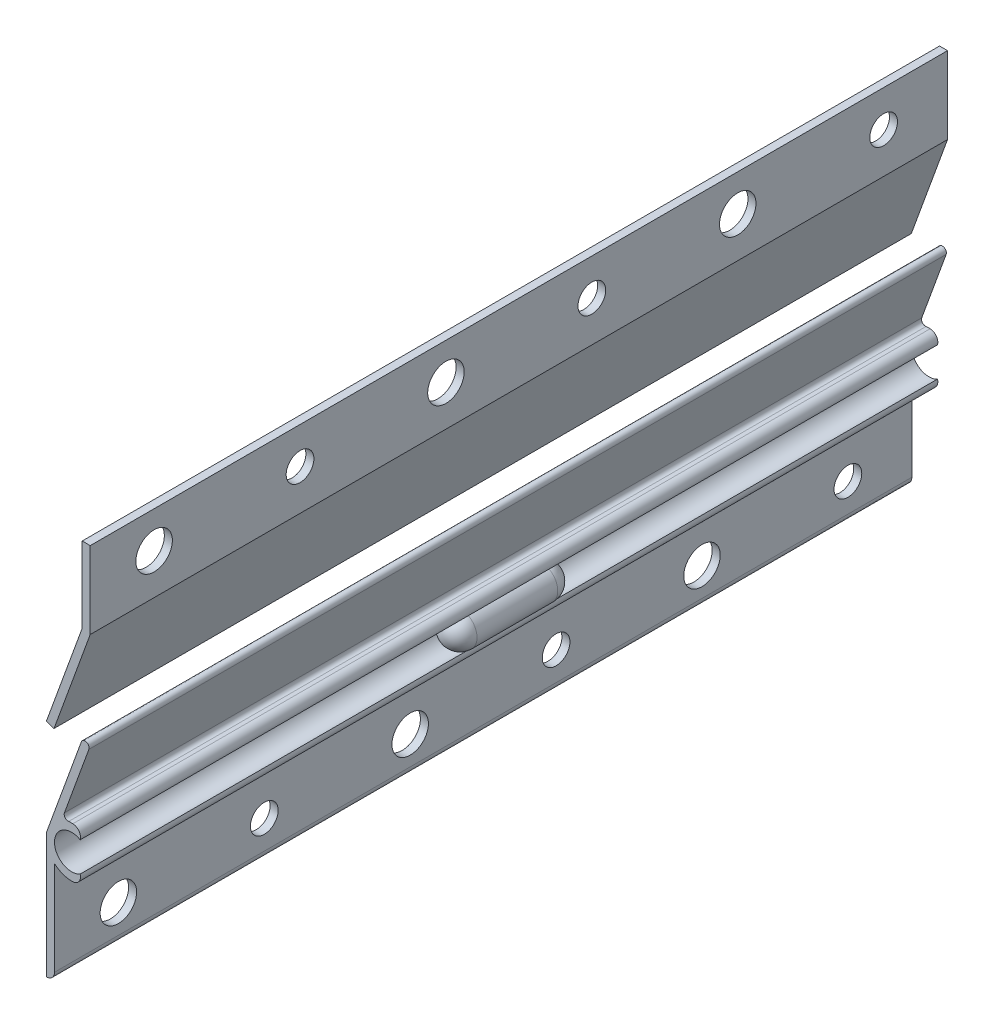
SolidWorks part; units mm, degrees
ref_plane "Front Plane" through (0, 0, 0) normal (0, 0, 1) x (1, 0, 0)
ref_plane "Top Plane" through (0, 0, 0) normal (0, 1, 0) x (1, 0, 0)
ref_plane "Right Plane" through (0, 0, 0) normal (1, 0, 0) x (0, 0, -1)
sketch "Sketch1" plane through (0, 0, 0) normal (0, 0, 1) x (1, 0, 0)
  line L0 (-3.81, -28.067) -> (-3.81, -6.2738) construction
  line L2 (-3.81, -28.067) -> (-2.413, -28.067) construction
  line L3 (-2.413, -28.067) -> (-2.413, -6.5201) construction
  line L4 (-2.413, -6.5201) -> (3.81, 10.5775) construction
  line L5 (3.81, 10.5775) -> (2.4972, 11.0553) construction
  line L6 (2.413, 28.067) -> (3.81, 28.067) construction
  line L7 (3.81, 28.067) -> (3.81, 14.662) construction
  line L9 (-2.4972, -2.667) -> (-3.81, -2.1892) construction
  line L10 (-3.81, -2.1892) -> (2.413, 14.9084) construction
  line L11 (2.413, 14.9084) -> (2.413, 28.067) construction
  line L12 (-3.81, -6.2738) -> (3.81, 14.662) construction
  line L13 (0, 28.067) -> (0, -28.067) construction
  line L14 (-3.81, 0) -> (3.81, 0) construction
  circle A0 centre (0.5689, -7.0459) radius 2.9819 construction
  circle A1 centre (0.5689, -7.0459) radius 4.3789 construction
  point P21 (0.5689, -2.667)
  dimension "Leaf Thickness" = 1.397
  dimension "Projection" = 7.62
  dimension "Length (C)" = 30.734
  dimension "Upper Leaf to Bottom" = 25.4
  dimension "D5" = 20
sketch "Sketch2" plane through (0, 0, 0) normal (1, 0, 0) x (0, 0, -1)
  line L0 (-74.6252, 28.067) -> (74.6252, 28.067) construction
  line L1 (-74.6252, 28.067) -> (-74.6252, 14.662) construction
  line L2 (-74.6252, 14.662) -> (74.6252, 14.662) construction
  line L3 (74.6252, 28.067) -> (74.6252, 14.662) construction
  line L4 (74.6252, -28.067) -> (-74.6252, -28.067) construction
  line L5 (74.6252, -28.067) -> (74.6252, -6.5201) construction
  line L6 (74.6252, -6.5201) -> (-74.6252, -6.5201) construction
  line L7 (-74.6252, -28.067) -> (-74.6252, -6.5201) construction
  line L8 (-12.7, 21.717) -> (12.7, 21.717) construction
  line L9 (0, 28.067) -> (0, -28.067) construction
  line L10 (-63.5, 21.717) -> (-63.5, 28.067) construction
  line L11 (-63.5, 21.717) -> (-38.1, 21.717) construction
  circle A0 centre (-63.5, 21.717) radius 3.175 construction
  circle A1 centre (-38.1, 21.717) radius 2.413 construction
  point P9 (152.4, 28.067)
  point P22 (0, -21.717)
  point P23 (0, 21.717)
  point P24 (-25.4, 21.717)
  point P25 (-50.8, 21.717)
  point P27 (25.4, 21.717)
  dimension "Large Mounting Hole" = 6.35
  dimension "Small Mounting Hole" = 4.826
  dimension "Length (A)" = 149.2504
  dimension "Hole Spacing" = 25.4
  dimension "Edge to Holes" = 6.35
  dimension "Number of Mounting Holes" = 304.8
  dimension "D5" = 6.35
  dimension "D1" = 50.8
  dimension "D2" = 25.4
  dimension "D3" = 38.1
sketch "Sketch3" plane through (0, 0, 0) normal (0, 0, 1) x (1, 0, 0)
  line L0 (-3.81, -2.1892) -> (-2.4972, -2.667)
  line L1 (-2.4972, -2.667) -> (3.81, 14.662)
  line L2 (3.81, 14.662) -> (3.81, 28.067)
  line L3 (3.81, 28.067) -> (2.413, 28.067)
  line L4 (2.413, 28.067) -> (2.413, 14.9084)
  line L5 (2.413, 14.9084) -> (-3.81, -2.1892)
extrude "Boss-Extrude1" add sketch "Sketch3" along normal up to vertex (74.6252 mm away) and the other way up to vertex (74.6252 mm away) up to point (0, 28.067, 74.6252) other way up to point (0, 28.067, -74.6252)
sketch "Sketch4" plane through (0, 0, 0) normal (0, 0, 1) x (1, 0, 0)
  line L0 (3.5711, 9.9211) -> (-0.6821, -1.7645)
  line L1 (-2.413, -10.2526) -> (-2.413, -26.67)
  line L3 (-3.81, -28.067) -> (-3.81, -6.2738)
  line L4 (-3.81, -6.2738) -> (2.2583, 10.3989)
  line L6 (-2.413, -6.5201) -> (3.81, 10.5775) construction
  line L7 (-3.81, -6.2738) -> (3.81, 14.662) construction
  line L8 (3.81, 10.5775) -> (2.4972, 11.0553) construction
  line L9 (-2.413, -28.067) -> (-2.413, -6.5201) construction
  line L10 (2.0598, -4.4635) -> (0.5689, -7.0459) construction
  arc A0 (2.2583, 10.3989) -> (3.5711, 9.9211) centre (2.9147, 10.16) cw
  arc A1 (-3.81, -28.067) -> (-2.413, -26.67) centre (-3.81, -26.67) ccw
  arc A3 (2.0598, -4.4635) -> (2.0598, -9.6282) centre (0.5689, -7.0459) ccw
  circle A4 centre (0.5689, -7.0459) radius 2.9819 construction
  arc A5 (-2.413, -10.2526) -> (0.7908, -11.4191) centre (0.5689, -7.0459) ccw
  arc A7 (2.0598, -9.6282) -> (0.7908, -11.4191) centre (0.72, -10.0239) cw
  arc A9 (-0.6821, -1.7645) -> (0.0561, -2.6971) centre (-0.0257, -2.0034) ccw
  arc A10 (0.0561, -2.6971) -> (0.7908, -2.6726) centre (0.5689, -7.0459) cw
  circle A11 centre (0.5689, -7.0459) radius 4.3789 construction
  arc A12 (2.0598, -4.4635) -> (0.7908, -2.6726) centre (0.72, -4.0678) ccw
  dimension "D1" = 60
extrude "Boss-Extrude2" add sketch "Sketch4" along normal up to vertex (74.6252 mm away) and the other way up to vertex (74.6252 mm away) separate body up to point (0, -6.5201, 74.6252) other way up to point (0, -6.5201, -74.6252)
ref_plane "Plane1" through (0.5689, 0, 0) normal (1, 0, 0) x (0, 0, -1)
sketch "Sketch5" plane through (0.5689, 0, 0) normal (1, 0, 0) x (0, 0, -1)
  line L0 (-10.0077, -7.0459) -> (10.0077, -7.0459)
  line L3 (-7.0259, -4.064) -> (-2.342, -4.064)
  line L4 (-2.342, -4.064) -> (2.342, -4.064)
  line L9 (10.0077, -7.0459) -> (30.0232, -7.0459) construction
  line L10 (2.342, -4.064) -> (7.0259, -4.064)
  arc A4 (-10.0077, -7.0459) -> (-7.0259, -4.064) centre (-7.0259, -7.0459) cw
  arc A5 (10.0077, -7.0459) -> (7.0259, -4.064) centre (7.0259, -7.0459) ccw
  point P0 (0, -4.064)
revolve "Revolve1" add sketch "Sketch5" angle 360 about L9
sketch "Sketch6" plane through (0, 0, 0) normal (1, 0, 0) x (0, 0, -1)
  line L0 (-63.5, 21.717) -> (-38.1, 21.717) construction
  line L1 (-63.5, 21.717) -> (-38.1, 21.717) construction
  circle A0 centre (-63.5, 21.717) radius 3.175
  circle A1 centre (-38.1, 21.717) radius 2.413
  circle A2 centre (-38.1, 21.717) radius 2.413 construction
  circle A3 centre (-63.5, 21.717) radius 3.175 construction
extrude "Cut-Extrude1" cut sketch "Sketch6" against normal through all both and the other way through all
pattern_linear "LPattern1" count 3 spacing 50.8 along (0, 0, -1) of "Cut-Extrude1"
sketch "Sketch7" plane through (0, 0, 0) normal (1, 0, 0) x (0, 0, -1)
  line L0 (-63.5, -21.717) -> (-38.1, -21.717) construction
  line L1 (-63.5, 21.717) -> (-38.1, 21.717) construction
  circle A0 centre (-63.5, -21.717) radius 3.175
  circle A1 centre (-38.1, -21.717) radius 2.413
  circle A2 centre (-38.1, 21.717) radius 2.413 construction
  circle A3 centre (-63.5, 21.717) radius 3.175 construction
extrude "Cut-Extrude2" cut sketch "Sketch7" against normal through all both and the other way through all
pattern_linear "LPattern2" count 3 spacing 50.8 along (0, 0, -1) of "Cut-Extrude2"
move or copy body "Body-Move/Copy2" bodies to move or copy 108 copy no translate (0, 6.35, 0) parameters "D1"=0, "D2"=6.35, "D3"=0
move or copy body "Body-Move/Copy3" bodies to move or copy 106 110 copy no translate (0, -6.35, 0) parameters "D1"=0, "D2"=6.35, "D3"=0
equation "\"D5@Sketch2\" = \"Edge to Holes@Sketch2\""
equation "\"D3@LPattern1\" = \"Hole Spacing@Sketch2\" * 2"
equation "\"D1@LPattern1\"=(\"Number of Mounting Holes@Sketch2\"/4)"
equation "\"D3@LPattern2\"=\"D3@LPattern1\""
equation "\"D1@LPattern2\"=\"D1@LPattern1\""
equation "\"D1@Sketch2\"=\"Hole Spacing@Sketch2\"*((\"Number of Mounting Holes@Sketch2\"/4)-1)"
equation "\"D2@Sketch2\"=\"Hole Spacing@Sketch2\""
equation "\"D3@Sketch2\"=\"D1@Sketch2\"-(\"Hole Spacing@Sketch2\"/2)"
